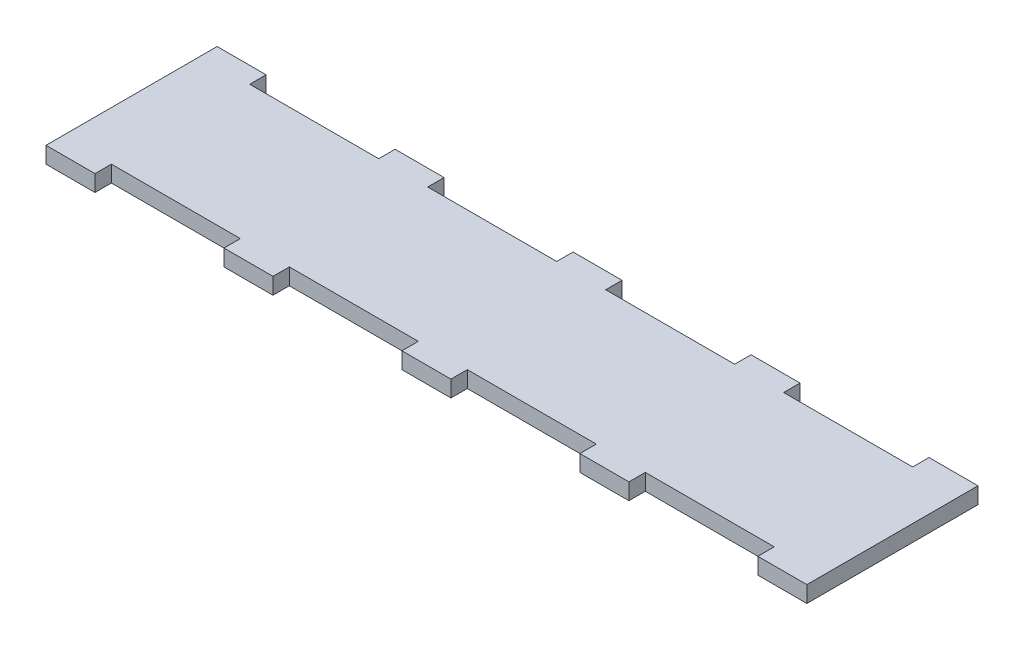
SolidWorks part; units mm, degrees
material "Beech"
ref_plane "Front Plane" through (0, 0, 0) normal (0, 0, 1) x (1, 0, 0)
ref_plane "Top Plane" through (0, 0, 0) normal (0, 1, 0) x (1, 0, 0)
ref_plane "Right Plane" through (0, 0, 0) normal (1, 0, 0) x (0, 0, -1)
sketch "Sketch1" plane through (0, 0, 0) normal (0, 1, 0) x (1, 0, 0)
  line L0 (69, -53.65) -> (69, -60)
  line L1 (19, 0) -> (69, 0)
  line L2 (0, 0) -> (0, -53.65)
  line L3 (19, -53.65) -> (69, -53.65)
  line L4 (295, 0) -> (295, -53.65)
  line L6 (0, -53.65) -> (0, -60)
  line L7 (0, -60) -> (19, -60)
  line L8 (19, -53.65) -> (19, -60)
  line L9 (69, -60) -> (88, -60)
  line L10 (88, -53.65) -> (88, -60)
  line L11 (138, -53.65) -> (138, -60)
  line L12 (138, -60) -> (157, -60)
  line L13 (157, -53.65) -> (157, -60)
  line L14 (207, -53.65) -> (207, -60)
  line L15 (207, -60) -> (226, -60)
  line L16 (226, -53.65) -> (226, -60)
  line L17 (276, -53.65) -> (276, -60)
  line L18 (276, -60) -> (295, -60)
  line L19 (295, -53.65) -> (295, -60)
  line L20 (88, -53.65) -> (138, -53.65)
  line L21 (157, -53.65) -> (207, -53.65)
  line L22 (226, -53.65) -> (276, -53.65)
  line L25 (0, 0) -> (0, 6.35)
  line L26 (0, 6.35) -> (19, 6.35)
  line L27 (19, 0) -> (19, 6.35)
  line L28 (69, 0) -> (69, 6.35)
  line L29 (69, 6.35) -> (88, 6.35)
  line L30 (88, 0) -> (88, 6.35)
  line L32 (138, 0) -> (138, 6.35)
  line L33 (138, 6.35) -> (157, 6.35)
  line L34 (157, 0) -> (157, 6.35)
  line L36 (207, 0) -> (207, 6.35)
  line L37 (207, 6.35) -> (226, 6.35)
  line L38 (226, 0) -> (226, 6.35)
  line L40 (276, 0) -> (276, 6.35)
  line L41 (276, 6.35) -> (295, 6.35)
  line L42 (295, 0) -> (295, 6.35)
  line L43 (88, 0) -> (138, 0)
  line L44 (157, 0) -> (207, 0)
  line L45 (226, 0) -> (276, 0)
  dimension "D1" = 295
  dimension "D2" = 53.65
  dimension "D3" = 19
  dimension "D4" = 6.35
  dimension "D6" = 6.35
  dimension "D7" = 19
  dimension "D5" = 5
extrude "Boss-Extrude1" add sketch "Sketch1" along normal blind 6.35
